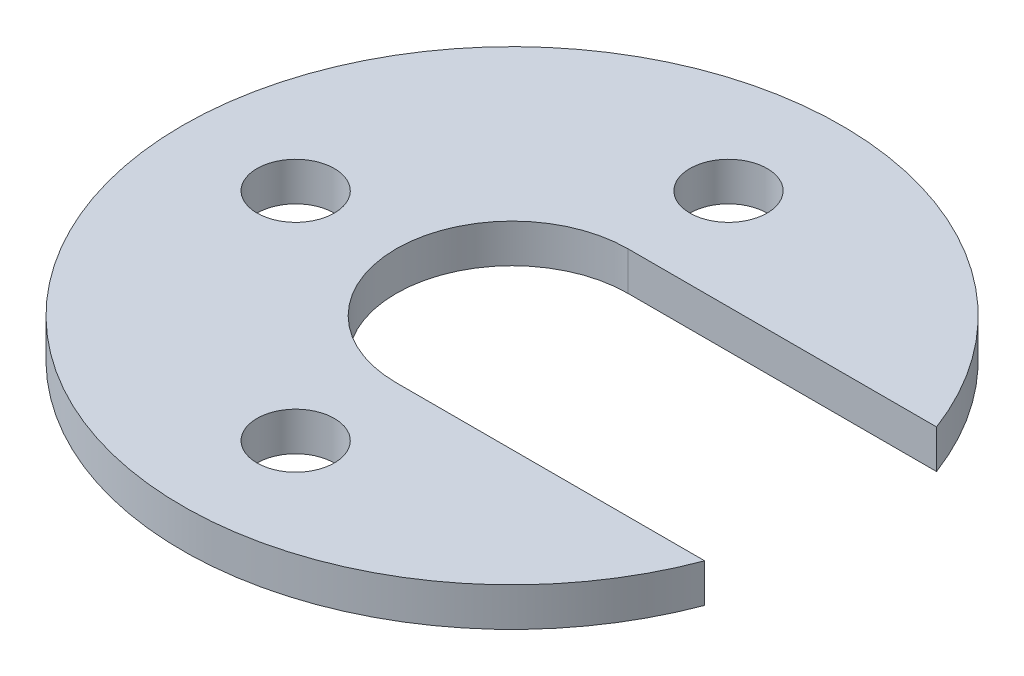
SolidWorks part; units mm, degrees
ref_plane "Front Plane" through (0, 0, 0) normal (0, 0, 1) x (1, 0, 0)
ref_plane "Top Plane" through (0, 0, 0) normal (0, 1, 0) x (1, 0, 0)
ref_plane "Right Plane" through (0, 0, 0) normal (1, 0, 0) x (0, 0, -1)
sketch "Sketch2" plane through (0, 0, 0) normal (0, 1, 0) x (1, 0, 0)
  line L0 (0, 58.2775) -> (0, -78.6411) construction
  line L1 (-74.777, 0) -> (77.4143, 0) construction
  line L2 (-28, 10.8638) -> (-28, -10.3635) construction
  line L3 (-7.6141, 28) -> (7.8911, 28) construction
  line L4 (-7.6141, -28) -> (7.8911, -28) construction
  line L5 (0, 15) -> (39.9172, 15)
  line L6 (0, -15) -> (39.9172, -15)
  arc A0 (39.9172, 15) -> (39.9172, -15) centre (0, 0) ccw
  circle A1 centre (0, 28) radius 5
  circle A2 centre (0, -28) radius 5
  circle A3 centre (-28, 0) radius 5
  arc A4 (0, 15) -> (0, -15) centre (0, 0) ccw
  dimension "D1" = 28
  dimension "D4" = 10
  dimension "D2" = 28
  dimension "D3" = 28
extrude "Boss-Extrude1" add sketch "Sketch2" along normal blind 5
